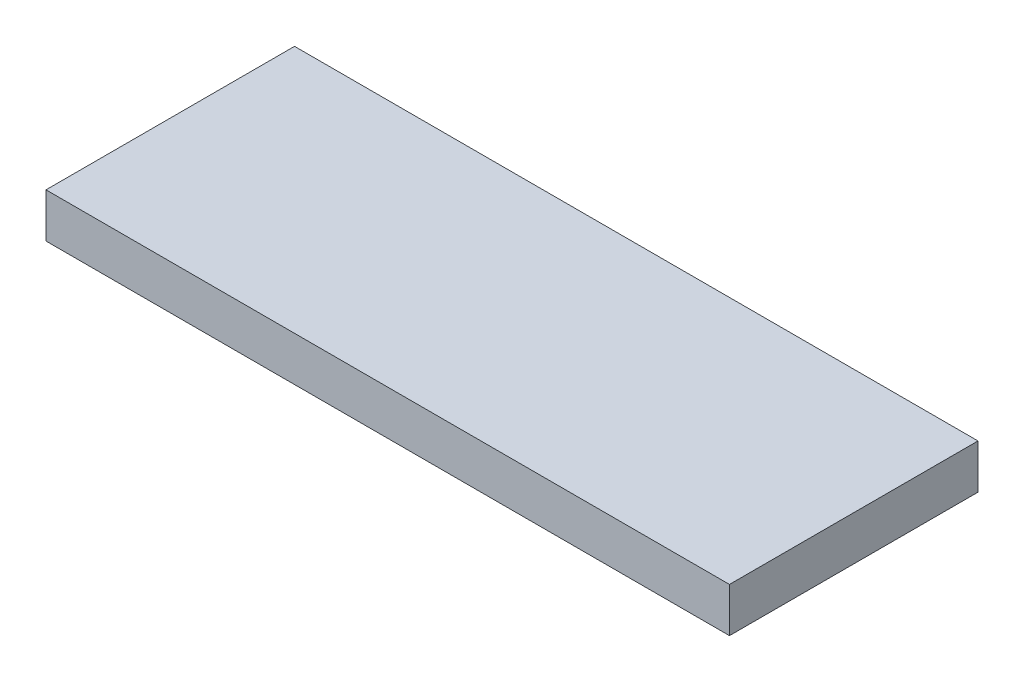
SolidWorks part; units mm, degrees
ref_plane "Front Plane" through (0, 0, 0) normal (0, 0, 1) x (1, 0, 0)
ref_plane "Top Plane" through (0, 0, 0) normal (0, 1, 0) x (1, 0, 0)
ref_plane "Right Plane" through (0, 0, 0) normal (1, 0, 0) x (0, 0, -1)
sketch "Sketch1" plane through (0, 0, 0) normal (0, 1, 0) x (1, 0, 0)
  line L1 (77, 28) -> (-77, 28)
  line L2 (77, 28) -> (77, -28)
  line L3 (77, -28) -> (-77, -28)
  line L4 (-77, 28) -> (-77, -28)
  line L5 (77, 28) -> (-77, -28) construction
  line L6 (77, -28) -> (-77, 28) construction
  point P0 (0, 0)
  dimension "D1" = 154
  dimension "D2" = 56
extrude "base" add sketch "Sketch1" along normal blind 10 contours L1 L4 L3 L2
sketch "Sketch2" plane through (0, 0, 0) normal (0, -1, 0) x (1, 0, 0)
  circle A0 centre (0, 0) radius 3
  dimension "D1" = 6
extrude "load cell button cut" [suppressed] cut sketch "Sketch2" against normal blind 2
sketch "Sketch4" plane through (0, 0, 0) normal (1, 0, 0) x (0, 0, -1)
  line L0 (3, 0) -> (3, 2)
  line L1 (3, 2) -> (0, 3.7321)
  line L2 (0, 3.7321) -> (0, 0) construction
  line L3 (0, 0) -> (3, 0)
  line L4 (0, 3.7321) -> (0, 0)
  dimension "D1" = 3
  dimension "D2" = 2
  dimension "D3" = 60
revolve "Cut-Revolve1" cut sketch "Sketch4" angle 360 about L2
equation "\"D2@Sketch1\"=46+10"
equation "\"D1@Sketch1\"=144+10"
